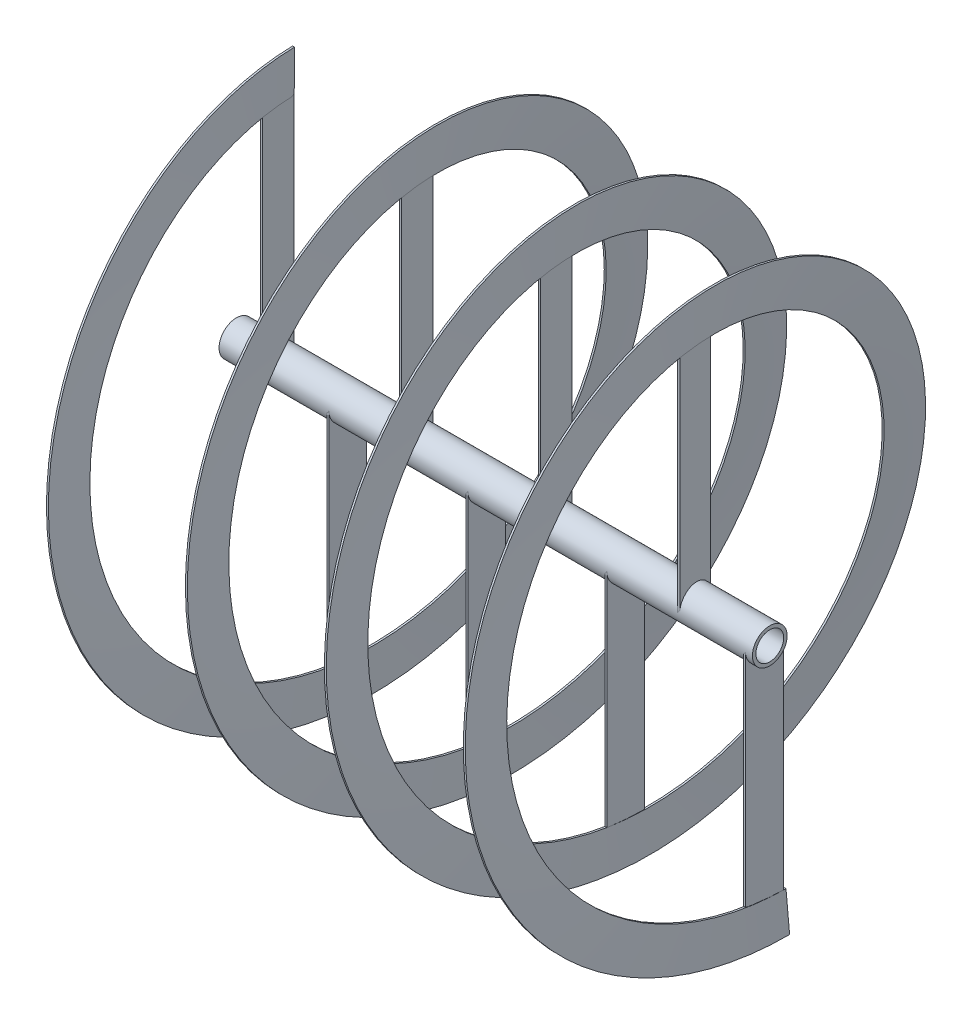
SolidWorks part; units mm, degrees
ref_plane "Plano frontal" through (0, 0, 0) normal (0, 0, 1) x (1, 0, 0)
ref_plane "Plano superior" through (0, 0, 0) normal (0, 1, 0) x (1, 0, 0)
ref_plane "Plano direito" through (0, 0, 0) normal (1, 0, 0) x (0, 0, -1)
sketch "Esboço1" plane through (0, 0, 0) normal (1, 0, 0) x (0, 0, -1)
  circle A0 centre (0, 0) radius 31.75
  circle A1 centre (0, 0) radius 25.4
  dimension "D1" = 63.5
  dimension "D2" = 50.8
extrude "Ressalto-extrusão1" add sketch "Esboço1" along normal mid plane 975
ref_plane "Plano1" through (-477.5, 0, 0) normal (-1, 0, 0) x (0, 0, 1)
sketch "Esboço3" plane through (-477.5, 0, 0) normal (-1, 0, 0) x (0, 0, 1)
  circle A0 centre (0, 0) radius 482.6
  dimension "D1" = 965.2
curve "Hélice/Espiral1" pitch 254 height 956 turns 3.7638
ref_plane "Plano2" through (0, 0, 0) normal (0, 1, 0) x (1, 0, 0)
sketch "Esboço4" plane through (0, 0, 0) normal (0, 1, 0) x (1, 0, 0)
  line L0 (-477.5, 26.4959) -> (-477.5, 482.6) construction
  line L1 (-477.5, 34.925) -> (-477.5, -34.925) construction
  line L2 (-487.5, 0) -> (487.5, 0) construction
  line L3 (-477.5, 482.6) -> (-474, 482.6)
  line L4 (-477.5, 482.6) -> (-477.5, 406.4)
  line L5 (-477.5, 406.4) -> (-474, 406.4)
  line L6 (-474, 482.6) -> (-474, 406.4)
  line L7 (-487.5, 31.75) -> (-487.5, -31.75) construction
  line L8 (487.5, -31.75) -> (487.5, 31.75) construction
  dimension "D1" = 76.2
  dimension "D2" = 3.5
  dimension "D3" = 965.2
sweep "Varredura1" add profiles "Esboço4" path "Hélice/Espiral1"
sketch "Esboço7" plane through (0, 0, 0) normal (1, 0, 0) x (0, 0, -1)
  line L0 (0, -482.6) -> (0, 482.6) construction
  line L1 (611.2768, 0) -> (-611.2768, 0) construction
  circle A0 centre (0, 0) radius 406.4 construction
  dimension "D2" = 76.2
  dimension "D1" = 965.2
sketch "Esboço8" plane through (0, 0, 0) normal (0, 0, 1) x (1, 0, 0)
  line L0 (-487.5, 482.6) -> (487.5, 482.6) construction
  line L1 (0, -482.6) -> (0, 482.6) construction
  line L2 (-487.5, 0) -> (883.2887, 0) construction
  line L3 (-487.5, 31.75) -> (-487.5, -31.75) construction
  line L4 (672.4045, 0) -> (-672.4045, 0) construction
  line L5 (672.4045, 0) -> (-672.4045, 0) construction
  line L6 (0, 482.6) -> (0, -586.3688) construction
  line L7 (-487.5, 406.4) -> (487.5, 406.4) construction
  line L8 (487.5, -31.75) -> (487.5, 31.75) construction
  line L9 (-487.5, -406.4) -> (487.5, -406.4) construction
  line L10 (-487.5, -482.6) -> (487.5, -482.6) construction
  dimension "D1" = 482.6
  dimension "D2" = 76.2
sketch3d "3DSketch3"
  line L0 (349.3323, 406.4, 0) -> (349.3323, 0, 0)
  line L1 (-487.5, 406.4, 0) -> (487.5, 406.4, 0) construction
  line L2 (-487.5, 0, 0) -> (883.2887, 0, 0) construction
  line L3 (95.3732, 406.4, 0) -> (95.3732, 0, 0)
  line L4 (-158.7142, 406.4, 0) -> (-158.7142, 0, 0)
  line L5 (-412.5902, 406.4, 0) -> (-412.5902, 0, 0)
  line L6 (222.3617, -406.4, 0) -> (222.3617, 0, 0)
  line L7 (-487.5, -406.4, 0) -> (487.5, -406.4, 0) construction
  line L8 (-31.6616, -406.4, 0) -> (-31.6616, 0, 0)
  line L9 (-285.65, -406.4, 0) -> (-285.65, 0, 0)
  line L10 (476.3523, -406.4, 0) -> (476.3523, 0, 0)
other "Barra cht BR CHT 3.5X2.5POL(1)"
ref_plane "Plano3" through (349.3323, 406.4, 0) normal (0, -1, 0) x (-0.9945, 0, 0.1045)
sketch "Sketch22" plane through (349.3323, 406.4, 0) normal (0, -1, 0) x (-0.9945, 0, 0.1045)
  line L8 (-1.75, -31.75) -> (1.75, -31.75)
  line L9 (-1.75, -31.75) -> (-1.75, 31.75)
  line L10 (-1.75, 31.75) -> (1.75, 31.75)
  line L11 (1.75, -31.75) -> (1.75, 31.75)
  line L12 (-1.75, -31.75) -> (1.75, 31.75) construction
  line L13 (-1.75, 31.75) -> (1.75, -31.75) construction
  point P0 (0, 0)
  point P5 (0, 0)
  dimension "D1" = 3.5
  dimension "D2" = 63.5
other "Barra cht BR CHT 3.5X2.5POL(3)"
ref_plane "Plano4" through (222.3617, -406.4, 0) normal (0, 1, 0) x (-0.9962, 0, -0.0872)
sketch "Sketch2" plane through (222.3617, -406.4, 0) normal (0, 1, 0) x (-0.9962, 0, -0.0872)
  line L8 (-1.75, -31.75) -> (1.75, -31.75)
  line L9 (-1.75, -31.75) -> (-1.75, 31.75)
  line L10 (-1.75, 31.75) -> (1.75, 31.75)
  line L11 (1.75, -31.75) -> (1.75, 31.75)
  line L12 (-1.75, -31.75) -> (1.75, 31.75) construction
  line L13 (-1.75, 31.75) -> (1.75, -31.75) construction
  point P0 (0, 0)
  point P5 (0, 0)
  dimension "D1" = 3.5
  dimension "D2" = 63.5
other "Barra cht BR CHT 3.5X2.5POL(4)"
ref_plane "Plano5" through (95.3732, 406.4, 0) normal (0, -1, 0) x (-0.9962, 0, 0.0872)
sketch "Sketch23" plane through (95.3732, 406.4, 0) normal (0, -1, 0) x (-0.9962, 0, 0.0872)
  line L8 (-1.75, -31.75) -> (1.75, -31.75)
  line L9 (-1.75, -31.75) -> (-1.75, 31.75)
  line L10 (-1.75, 31.75) -> (1.75, 31.75)
  line L11 (1.75, -31.75) -> (1.75, 31.75)
  line L12 (-1.75, -31.75) -> (1.75, 31.75) construction
  line L13 (-1.75, 31.75) -> (1.75, -31.75) construction
  point P0 (0, 0)
  point P5 (0, 0)
  dimension "D1" = 3.5
  dimension "D2" = 63.5
other "Barra cht BR CHT 3.5X2.5POL(5)"
ref_plane "Plano6" through (-31.6616, -406.4, 0) normal (0, 1, 0) x (-0.9962, 0, -0.0872)
sketch "Sketch24" plane through (-31.6616, -406.4, 0) normal (0, 1, 0) x (-0.9962, 0, -0.0872)
  line L8 (-1.75, -31.75) -> (1.75, -31.75)
  line L9 (-1.75, -31.75) -> (-1.75, 31.75)
  line L10 (-1.75, 31.75) -> (1.75, 31.75)
  line L11 (1.75, -31.75) -> (1.75, 31.75)
  line L12 (-1.75, -31.75) -> (1.75, 31.75) construction
  line L13 (-1.75, 31.75) -> (1.75, -31.75) construction
  point P0 (0, 0)
  point P5 (0, 0)
  dimension "D1" = 3.5
  dimension "D2" = 63.5
other "Barra cht BR CHT 3.5X2.5POL(6)"
ref_plane "Plano7" through (-158.7142, 406.4, 0) normal (0, -1, 0) x (-0.9962, 0, 0.0872)
sketch "Sketch25" plane through (-158.7142, 406.4, 0) normal (0, -1, 0) x (-0.9962, 0, 0.0872)
  line L8 (-1.75, -31.75) -> (1.75, -31.75)
  line L9 (-1.75, -31.75) -> (-1.75, 31.75)
  line L10 (-1.75, 31.75) -> (1.75, 31.75)
  line L11 (1.75, -31.75) -> (1.75, 31.75)
  line L12 (-1.75, -31.75) -> (1.75, 31.75) construction
  line L13 (-1.75, 31.75) -> (1.75, -31.75) construction
  point P0 (0, 0)
  point P5 (0, 0)
  dimension "D1" = 3.5
  dimension "D2" = 63.5
other "Barra cht BR CHT 3.5X2.5POL(7)"
ref_plane "Plano8" through (-285.65, -406.4, 0) normal (0, 1, 0) x (-0.9962, 0, -0.0872)
sketch "Sketch26" plane through (-285.65, -406.4, 0) normal (0, 1, 0) x (-0.9962, 0, -0.0872)
  line L8 (-1.75, -31.75) -> (1.75, -31.75)
  line L9 (-1.75, -31.75) -> (-1.75, 31.75)
  line L10 (-1.75, 31.75) -> (1.75, 31.75)
  line L11 (1.75, -31.75) -> (1.75, 31.75)
  line L12 (-1.75, -31.75) -> (1.75, 31.75) construction
  line L13 (-1.75, 31.75) -> (1.75, -31.75) construction
  point P0 (0, 0)
  point P5 (0, 0)
  dimension "D1" = 3.5
  dimension "D2" = 63.5
other "Barra cht BR CHT 3.5X2.5POL(8)"
ref_plane "Plano9" through (-412.5902, 406.4, 0) normal (0, -1, 0) x (-0.9962, 0, 0.0872)
sketch "Sketch27" plane through (-412.5902, 406.4, 0) normal (0, -1, 0) x (-0.9962, 0, 0.0872)
  line L8 (-1.75, -31.75) -> (1.75, -31.75)
  line L9 (-1.75, -31.75) -> (-1.75, 31.75)
  line L10 (-1.75, 31.75) -> (1.75, 31.75)
  line L11 (1.75, -31.75) -> (1.75, 31.75)
  line L12 (-1.75, -31.75) -> (1.75, 31.75) construction
  line L13 (-1.75, 31.75) -> (1.75, -31.75) construction
  point P0 (0, 0)
  point P5 (0, 0)
  dimension "D1" = 3.5
  dimension "D2" = 63.5
other "Barra cht BR CHT 3.5X2.5POL(10)"
ref_plane "Plano10" through (476.3523, -406.4, 0) normal (0, 1, 0) x (-0.9945, 0, -0.1045)
sketch "Sketch28" plane through (476.3523, -406.4, 0) normal (0, 1, 0) x (-0.9945, 0, -0.1045)
  line L8 (-1.75, -31.75) -> (1.75, -31.75)
  line L9 (-1.75, -31.75) -> (-1.75, 31.75)
  line L10 (-1.75, 31.75) -> (1.75, 31.75)
  line L11 (1.75, -31.75) -> (1.75, 31.75)
  line L12 (-1.75, -31.75) -> (1.75, 31.75) construction
  line L13 (-1.75, 31.75) -> (1.75, -31.75) construction
  point P0 (0, 0)
  point P5 (0, 0)
  dimension "D1" = 3.5
  dimension "D2" = 63.5
ref_plane "Plano11" through (-500, 0, 0) normal (1, 0, 0) x (0, 0, -1)
sketch "Esboço19" plane through (-500, 0, 0) normal (1, 0, 0) x (0, 0, -1)
  line L1 (31.7817, 0) -> (631.7817, 0)
  line L2 (31.7817, 0) -> (31.7817, 550)
  line L3 (31.7817, 550) -> (631.7817, 550)
  line L4 (631.7817, 0) -> (631.7817, 550)
  dimension "D1" = 600
  dimension "D2" = 550
extrude "Corte-extrusão2" cut sketch "Esboço19" along normal blind 112
sketch "Esboço20" plane through (487.5, 0, 0) normal (1, 0, 0) x (0, 0, -1)
  circle A0 centre (0, 0) radius 31.75
  dimension "D1" = 63.5
extrude "Corte-extrusão3" cut sketch "Esboço20" against normal blind 1193
